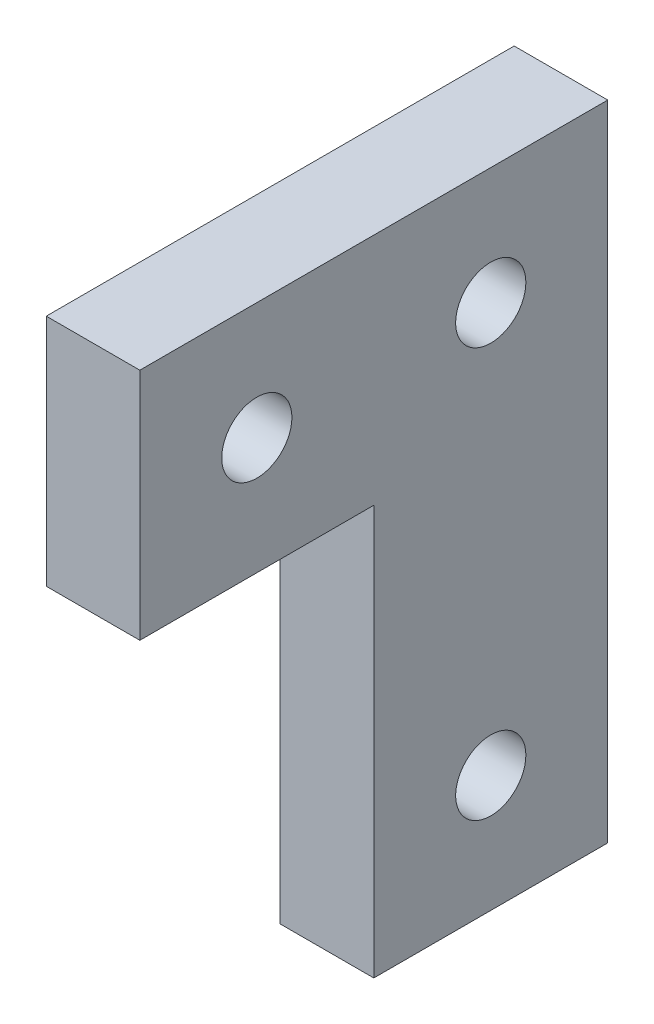
SolidWorks part; units mm, degrees
ref_plane "前视基准面" through (0, 0, 0) normal (0, 0, 1) x (1, 0, 0)
ref_plane "上视基准面" through (0, 0, 0) normal (0, 1, 0) x (1, 0, 0)
ref_plane "右视基准面" through (0, 0, 0) normal (1, 0, 0) x (0, 0, -1)
other "Configuration Table"
sketch "草图1" plane through (0, 0, 0) normal (1, 0, 0) x (0, 0, -1)
  line L0 (-6, -2) -> (-2, -2)
  line L1 (-6, 2) -> (2, 2)
  line L2 (-6, 2) -> (-6, -9)
  line L3 (-6, -9) -> (2, -9)
  line L4 (2, 2) -> (2, -9)
  line L5 (-2, -9) -> (-2, -2)
  circle A0 centre (0, 0) radius 0.6
  circle A1 centre (-4, 0) radius 0.6
  circle A2 centre (0, -7) radius 0.6
  dimension "D1" = 1.2
  dimension "D10" = 1.2
  dimension "D2" = 2
  dimension "D3" = 6
  dimension "D4" = 9
  dimension "D5" = 2
  dimension "D6" = 2
  dimension "D7" = 2
  dimension "D8" = 2
  dimension "D9" = 2
extrude "凸台-拉伸1" add sketch "草图1" along normal blind 1.6 contours L5 L3 L4 L1 L2 L0 A2 A1 A0
